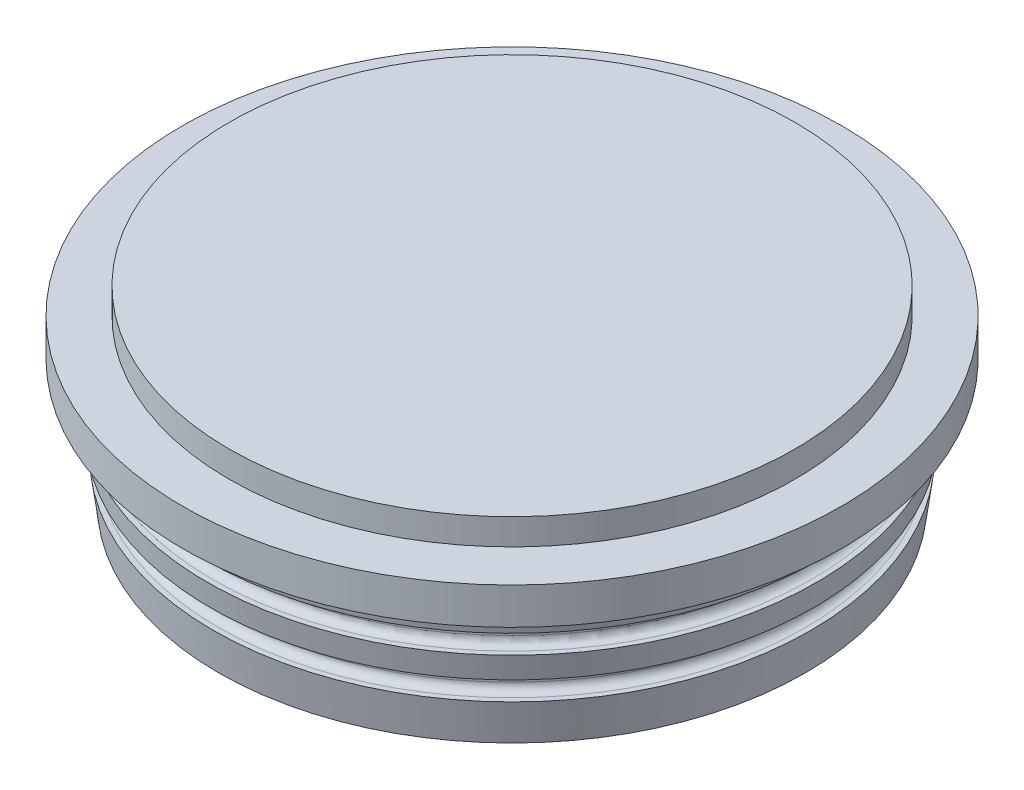
SolidWorks part; units mm, degrees
ref_plane "Plan de face" through (0, 0, 0) normal (0, 0, 1) x (1, 0, 0)
ref_plane "Plan de dessus" through (0, 0, 0) normal (0, 1, 0) x (1, 0, 0)
ref_plane "Plan de droite" through (0, 0, 0) normal (1, 0, 0) x (0, 0, -1)
sketch "Esquisse1" plane through (0, 0, 0) normal (0, 0, 1) x (1, 0, 0)
  line L0 (56, -31) -> (59.1597, -7) construction
  line L6 (0, 0) -> (0, 368.3817) construction
  line L7 (0, 0) -> (449.1686, 0) construction
  line L16 (65.9492, -289.476) -> (65.9492, -272.476) construction
  line L18 (59.1597, -7) -> (62.9, -7)
  line L26 (56, -31) -> (56, -7) construction
  line L27 (56, -7) -> (59.1597, -7) construction
  line L29 (62.9, 0) -> (0, 0) construction
  line L30 (0, 0) -> (0, -6.5)
  line L31 (0, -6.5) -> (47, -6.5)
  line L32 (47, -6.5) -> (47, -31)
  line L33 (47, -31) -> (56, -31)
  line L34 (56, -31) -> (56.9874, -23.5)
  line L35 (56.9874, -23.5) -> (54.514, -23.5)
  line L36 (54.514, -23.5) -> (54.514, -19.5)
  line L37 (54.514, -19.5) -> (57.514, -19.5)
  line L38 (57.514, -19.5) -> (58.1064, -15)
  line L39 (58.1064, -15) -> (55.633, -15)
  line L40 (55.633, -15) -> (55.633, -11)
  line L41 (55.633, -11) -> (58.633, -11)
  line L42 (58.633, -11) -> (59.1597, -7)
  line L43 (62.9, -7) -> (62.9, 0)
  line L44 (62.9, 0) -> (54, 0)
  line L45 (54, 0) -> (54, 5)
  line L46 (54, 5) -> (0, 5)
  line L47 (0, 5) -> (0, 0)
  point P13 (47.0737, -5.4886)
  point P16 (65.9492, 0)
  point P26 (0, 0)
  point P27 (64.1597, 0.1325)
  dimension "D2" = 47
  dimension "D3" = 7.5
  dimension "D4" = 24
  dimension "D5" = 6.5
  dimension "D6" = 7.5
  dimension "D8" = 56
  dimension "D9" = 7
  dimension "D10" = 8.5
  dimension "D11" = 5
  dimension "D12" = 4
  dimension "D13" = 3
  dimension "D14" = 54
  dimension "D15" = 47
  dimension "D16" = 62.9
revolve "Révolution1" add sketch "Esquisse1" angle 360 about L6
fillet "Congé1" radius 1.5 4 edges at (0, -15, -55.633) (0, -23.5, -54.514) (0, -19.5, -54.514) (0, -11, -55.633)
fillet "Congé2" radius 10 1 edges at (0, -6.5, -47)
equation "\"é\"=1"
